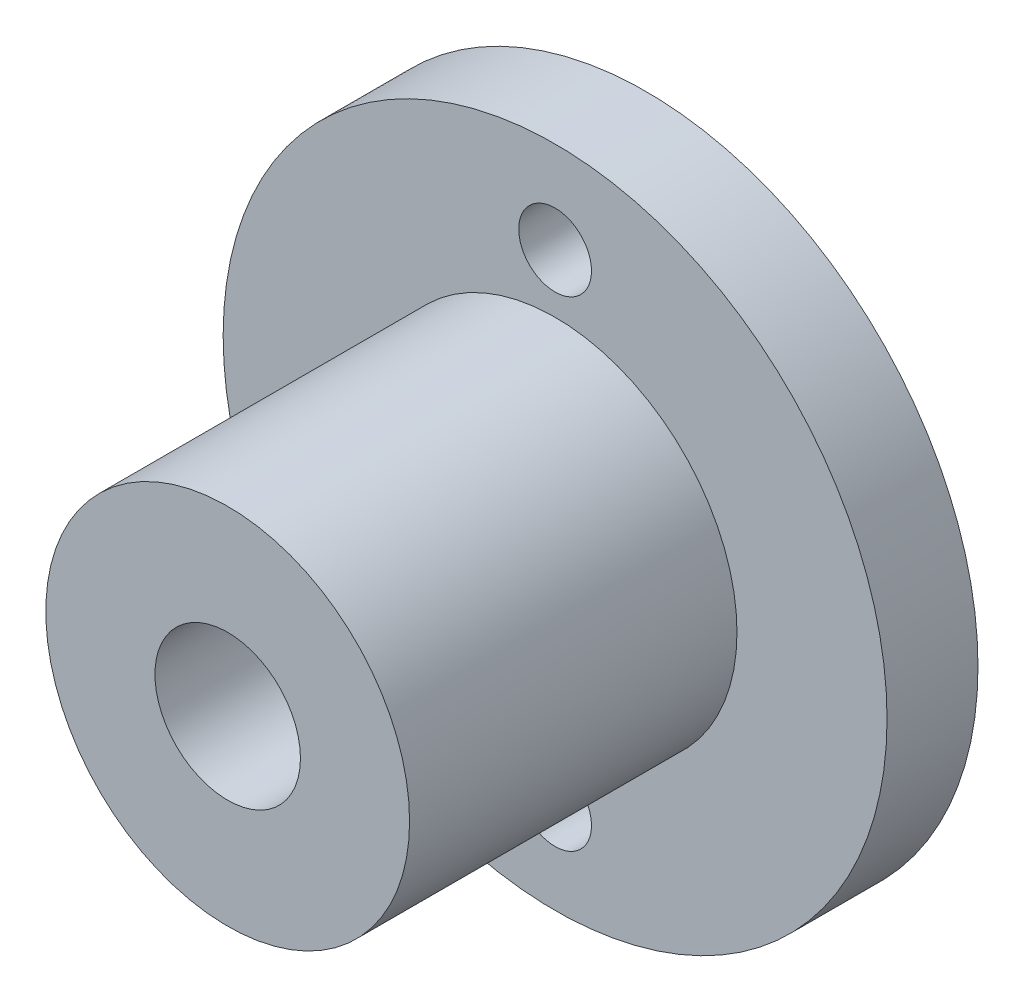
SolidWorks part; units mm, degrees
ref_plane "Alzado" through (0, 0, 0) normal (0, 0, 1) x (1, 0, 0)
ref_plane "Planta" through (0, 0, 0) normal (0, 1, 0) x (1, 0, 0)
ref_plane "Vista lateral" through (0, 0, 0) normal (1, 0, 0) x (0, 0, -1)
sketch "Croquis1" plane through (0, 0, 0) normal (0, 0, 1) x (1, 0, 0)
  line L0 (0, 0) -> (0, 50000) construction
  line L1 (0, 0) -> (50000, 0) construction
  circle A0 centre (0, 0) radius 18.25
  circle A1 centre (0, 13.2) radius 2
  circle A2 centre (0, -13.2) radius 2
extrude "Saliente-Extruir2" add sketch "Croquis1" against normal blind 5
sketch "Croquis2" plane through (0, 0, 0) normal (0, 0, 1) x (1, 0, 0)
  circle A0 centre (0, 0) radius 10
extrude "Saliente-Extruir4" add sketch "Croquis2" along normal blind 18
sketch "Croquis3" plane through (0, 0, 18) normal (0, 0, 1) x (1, 0, 0)
  circle A0 centre (0, 0) radius 4
extrude "Cortar-Extruir1" cut sketch "Croquis3" against normal blind 23
